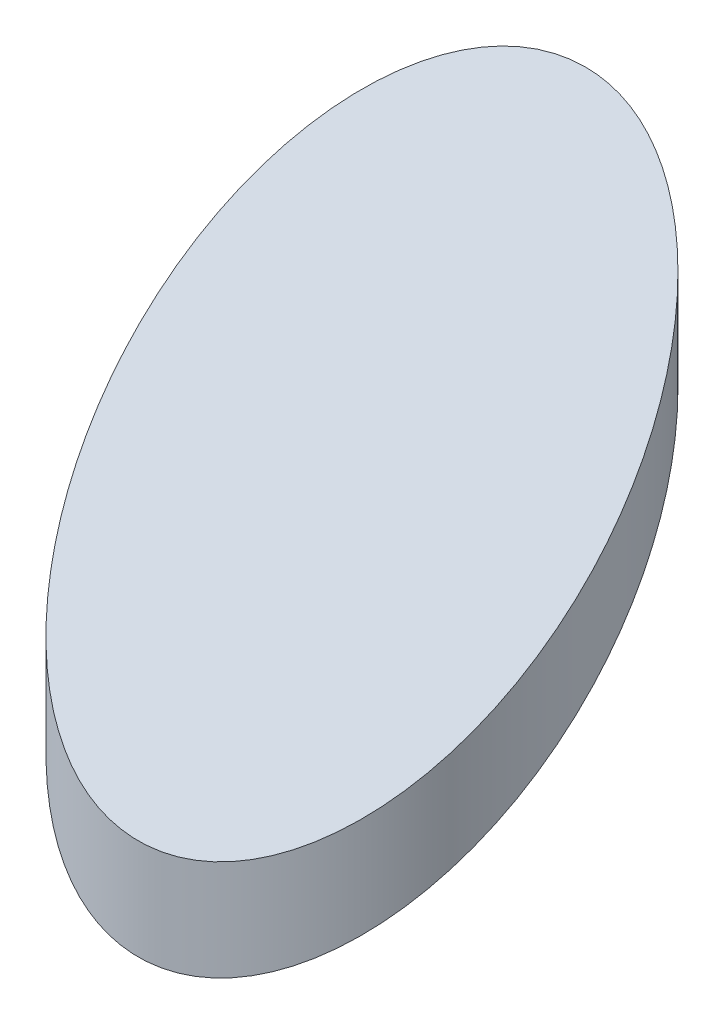
SolidWorks part; units mm, degrees
material "PTFE (general)"
ref_plane "Front Plane" through (0, 0, 0) normal (0, 0, 1) x (1, 0, 0)
ref_plane "Top Plane" through (0, 0, 0) normal (0, 1, 0) x (1, 0, 0)
ref_plane "Right Plane" through (0, 0, 0) normal (1, 0, 0) x (0, 0, -1)
sketch "Sketch1" plane through (0, 0, 0) normal (0, 1, 0) x (1, 0, 0)
  line L0 (-102.6662, 0) -> (114.9528, 0) construction
  line L1 (-55, 0) -> (55, 0) construction
ref_plane "Plane1" through (0, 0, 0) normal (0, 0.7071, 0.7071) x (1, 0, 0)
sketch "Sketch2" plane through (0, 0, 0) normal (0, 0.7071, 0.7071) x (1, 0, 0)
  circle A0 centre (0, 20) radius 20
  dimension "D1" = 40
extrude "Boss-Extrude1" add sketch "Sketch2" against normal blind 2
ref_plane "Plane2" through (0, -3.25, 0) normal (0, 1, 0) x (1, 0, 0)
sketch "Sketch6" plane through (0, 0, 0) normal (0, 1, 0) x (1, 0, 0)
  circle A0 centre (0, 9) radius 6.28
  circle A1 centre (0, 9) radius 25.0596
  dimension "D1" = 12.56
  dimension "D2" = 9
extrude "Cut-Extrude2" cut sketch "Sketch6" against normal through all both and the other way through all
sketch "Sketch3" plane through (0, -3.25, 0) normal (0, 1, 0) x (1, 0, 0)
  line L0 (0, -15.8313) -> (0, 15.8313) construction
  circle A0 centre (0, 7.4) radius 7.4
  circle A1 centre (0, 7.4) radius 5.9
  dimension "D1" = 14.8
  dimension "D2" = 11.8
extrude "Boss-Extrude2" add sketch "Sketch3" along normal blind 1 separate body
sketch "Sketch7" plane through (0, -3.25, 0) normal (0, -1, 0) x (1, 0, 0)
  circle A0 centre (0.2909, -7.5174) radius 13.0221
extrude "Cut-Extrude3" cut sketch "Sketch7" against normal blind 1
